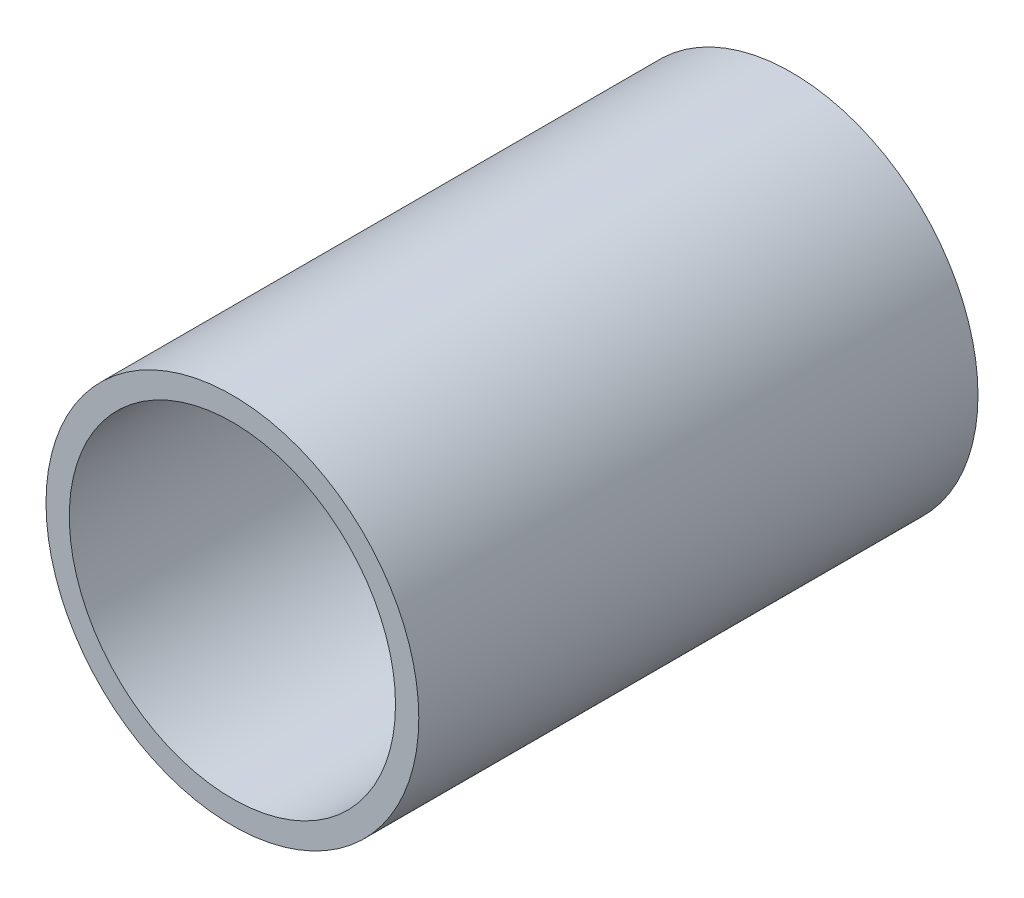
SolidWorks part; units mm, degrees
ref_plane "Plano frontal" through (0, 0, 0) normal (0, 0, 1) x (1, 0, 0)
ref_plane "Plano superior" through (0, 0, 0) normal (0, 1, 0) x (1, 0, 0)
ref_plane "Plano direito" through (0, 0, 0) normal (1, 0, 0) x (0, 0, -1)
sketch "Esboço2" plane through (0, 0, 0) normal (0, 0, 1) x (1, 0, 0)
  circle A0 centre (0, 0) radius 7
  circle A2 centre (0, 0) radius 8
  dimension "D1" = 14
  dimension "D2" = 16
extrude "Ressalto-extrusão2" add sketch "Esboço2" along normal blind 24
